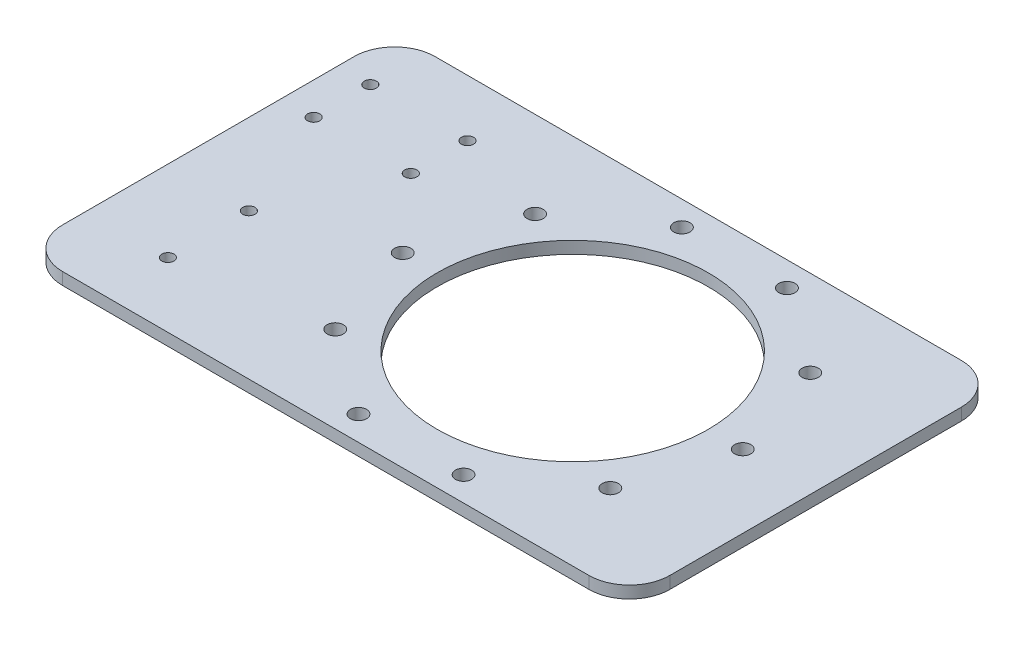
SolidWorks part; units mm, degrees
ref_plane "前基準面" through (0, 0, 0) normal (0, 0, 1) x (1, 0, 0)
ref_plane "上基準面" through (0, 0, 0) normal (0, 1, 0) x (1, 0, 0)
ref_plane "右基準面" through (0, 0, 0) normal (1, 0, 0) x (0, 0, -1)
sketch "草圖1" plane through (0, 0, 0) normal (0, 1, 0) x (1, 0, 0)
  line L1 (-75, 46) -> (75, 46)
  line L2 (-75, 46) -> (-75, -46)
  line L3 (-75, -46) -> (75, -46)
  line L4 (75, 46) -> (75, -46)
  line L5 (-75, 46) -> (75, -46) construction
  line L6 (-75, -46) -> (75, 46) construction
  circle A0 centre (15, 0) radius 33.5
  point P0 (0, 0)
  dimension "D3" = 67
  dimension "D1" = 92
  dimension "D2" = 150
  dimension "D4" = 15
extrude "填料-伸長1" add sketch "草圖1" along normal blind 3
sketch "草圖2" plane through (0, 3, 0) normal (0, 1, 0) x (1, 0, 0)
  circle A0 centre (15, 0) radius 42 construction
  circle A1 centre (15, 0) radius 33.5 construction
  circle A2 centre (57, 0) radius 2
  dimension "D1" = 84
  dimension "D2" = 4
extrude "除料-伸長1" cut sketch "草圖2" against normal up to next
pattern_circular "環狀複製排列1" count 10 over 360 about axis through (15, 0, 0) along (0, 1, 0) of "除料-伸長1"
sketch "草圖3" plane through (0, 3, 0) normal (0, 1, 0) x (1, 0, 0)
  line L0 (-75, 46) -> (-75, -46) construction
  line L1 (-75, 40) -> (-35, 40) construction
  line L2 (-75, 40) -> (-75, -40) construction
  line L3 (-75, -40) -> (-35, -40) construction
  line L4 (-35, 40) -> (-35, -40) construction
  line L5 (-75, 40) -> (-35, -40) construction
  line L6 (-75, -40) -> (-35, 40) construction
  line L7 (-75, 10) -> (-35, 10) construction
  line L8 (-55, 40) -> (-55, 10) construction
  circle A0 centre (-67, 32) radius 1.5
  circle A1 centre (-67, 18) radius 1.5
  circle A2 centre (-43, 18) radius 1.5
  circle A3 centre (-43, 32) radius 1.5
  circle A4 centre (-55, -10) radius 1.5
  circle A5 centre (-55, -30) radius 1.5
  point P0 (-55, 0)
  dimension "D7" = 3
  dimension "D1" = 40
  dimension "D2" = 80
  dimension "D3" = 30
  dimension "D4" = 8
  dimension "D5" = 8
  dimension "D6" = 8
  dimension "D8" = 20
  dimension "D9" = 20
extrude "除料-伸長2" cut sketch "草圖3" against normal blind 3
fillet "圓角1" radius 10 4 edges at (-75, 1.5, -46) (-75, 1.5, 46) (75, 1.5, 46) (75, 1.5, -46)
